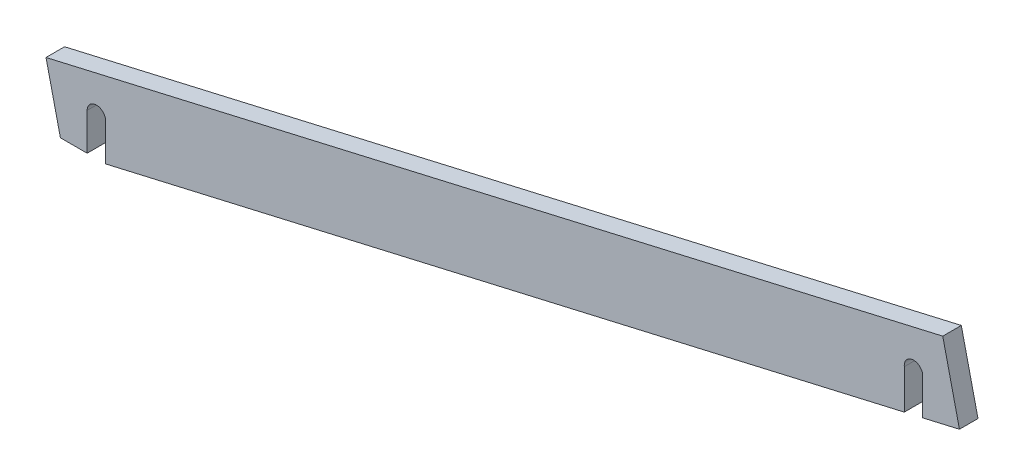
SolidWorks part; units mm, degrees
material "G10"
ref_plane "Front Plane" through (0, 0, 0) normal (0, 0, 1) x (1, 0, 0)
ref_plane "Top Plane" through (0, 0, 0) normal (0, 1, 0) x (1, 0, 0)
ref_plane "Right Plane" through (0, 0, 0) normal (1, 0, 0) x (0, 0, -1)
sketch "Sketch1" plane through (0, 0, 0) normal (0, 0, 1) x (1, 0, 0)
  line L0 (0, 0) -> (0, 3.175)
  line L1 (0, 0) -> (10.7112, 0) construction
  line L2 (1.5875, 3.175) -> (1.5875, 0)
  line L3 (1.5875, 0) -> (69.9135, 15.7743)
  line L4 (69.9135, 15.7743) -> (69.9135, 19.1469)
  line L5 (74.6319, 16.8636) -> (73.2035, 23.0509)
  line L6 (71.4922, 19.3138) -> (71.4922, 16.1388)
  line L7 (71.4922, 16.1388) -> (74.6319, 16.8636)
  line L8 (1.5875, 6.517) -> (-3.5184, 5.3382)
  line L9 (0, 0) -> (-2.286, 0)
  line L12 (1.5875, 6.517) -> (73.2035, 23.0509)
  line L13 (1.5875, 3.175) -> (1.5875, 8.4014) construction
  line L14 (-2.286, 0) -> (-3.5184, 5.3382)
  arc A0 (69.9135, 19.1469) -> (71.4922, 19.3138) centre (70.7029, 19.2303) cw
  arc A1 (0, 3.175) -> (1.5875, 3.175) centre (0.7937, 3.175) cw
extrude "Boss-Extrude1" add sketch "Sketch1" along normal blind 1.5875
